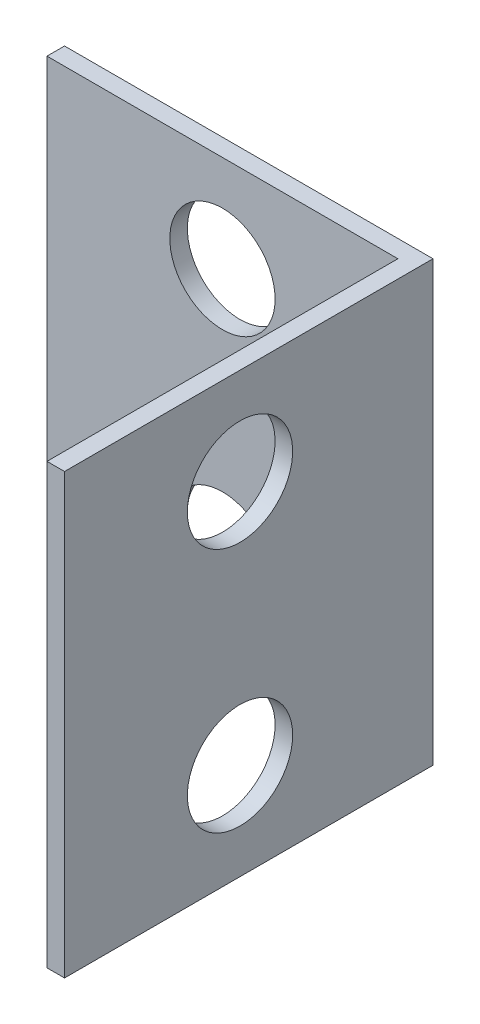
SolidWorks part; units mm, degrees
ref_plane "Front Plane" through (0, 0, 0) normal (0, 0, 1) x (1, 0, 0)
ref_plane "Top Plane" through (0, 0, 0) normal (0, 1, 0) x (1, 0, 0)
ref_plane "Right Plane" through (0, 0, 0) normal (1, 0, 0) x (0, 0, -1)
sketch "Sketch1" plane through (0, 0, 0) normal (0, 0, 1) x (1, 0, 0)
  line L1 (-10, -12.5) -> (10, -12.5)
  line L2 (-10, -12.5) -> (-10, 12.5)
  line L3 (-10, 12.5) -> (10, 12.5)
  line L4 (10, -12.5) -> (10, 12.5)
  line L5 (-10, -12.5) -> (10, 12.5) construction
  line L6 (-10, 12.5) -> (10, -12.5) construction
  point P0 (0, 0)
  dimension "D1" = 20
  dimension "D2" = 25
extrude "Boss-Extrude1" add sketch "Sketch1" along normal blind 1
sketch "Sketch3" plane through (10, 0, 0) normal (1, 0, 0) x (0, 0, -1)
  line L1 (0, 12.5) -> (-21, 12.5)
  line L2 (0, 12.5) -> (0, -12.5)
  line L3 (0, -12.5) -> (-21, -12.5)
  line L4 (-21, 12.5) -> (-21, -12.5)
  dimension "D1" = 21
  dimension "D2" = 25
extrude "Boss-Extrude2" add sketch "Sketch3" along normal blind 1
sketch "Sketch4" plane through (0, 0, 1) normal (0, 0, 1) x (1, 0, 0)
  line L0 (0, 0) -> (0, 12.5) construction
  line L1 (10, 12.5) -> (-10, 12.5) construction
  line L2 (-10, 0) -> (10, 0) construction
  line L3 (-10, 12.5) -> (-10, -12.5) construction
  line L4 (10, -12.5) -> (10, 12.5) construction
  circle A0 centre (0, 7) radius 3
  circle A1 centre (0, -7) radius 3
  dimension "D1" = 6
  dimension "D2" = 7
extrude "Cut-Extrude1" cut sketch "Sketch4" against normal through all
sketch "Sketch5" plane through (10, 0, 0) normal (-1, 0, 0) x (0, 0, 1)
  line L0 (21, 0) -> (1, 0) construction
  line L1 (21, 12.5) -> (21, -12.5) construction
  line L2 (1, -12.5) -> (1, 12.5) construction
  line L3 (11, 0) -> (11, 12.5) construction
  line L4 (1, 12.5) -> (21, 12.5) construction
  circle A0 centre (11, 7) radius 3
  circle A1 centre (11, -7) radius 3
  dimension "D1" = 6
  dimension "D2" = 7
extrude "Cut-Extrude2" cut sketch "Sketch5" against normal through all
